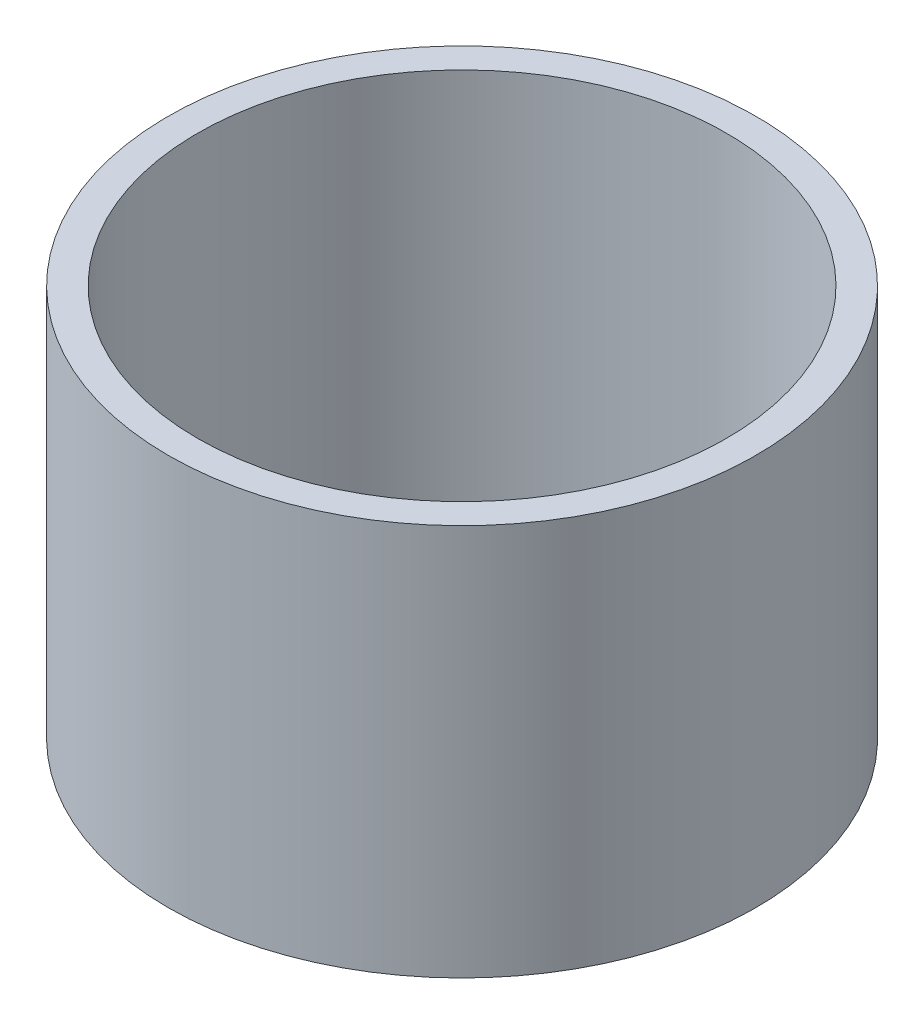
SolidWorks part; units mm, degrees
ref_plane "前视基准面" through (0, 0, 0) normal (0, 0, 1) x (1, 0, 0)
ref_plane "上视基准面" through (0, 0, 0) normal (0, 1, 0) x (1, 0, 0)
ref_plane "右视基准面" through (0, 0, 0) normal (1, 0, 0) x (0, 0, -1)
sketch "草图1" plane through (0, 0, 0) normal (0, 1, 0) x (1, 0, 0)
  circle A0 centre (0, 0) radius 15
  circle A1 centre (0, 0) radius 13.5
  dimension "D1" = 27
  dimension "D2" = 30
extrude "凸台-拉伸1" add sketch "草图1" along normal blind 20
